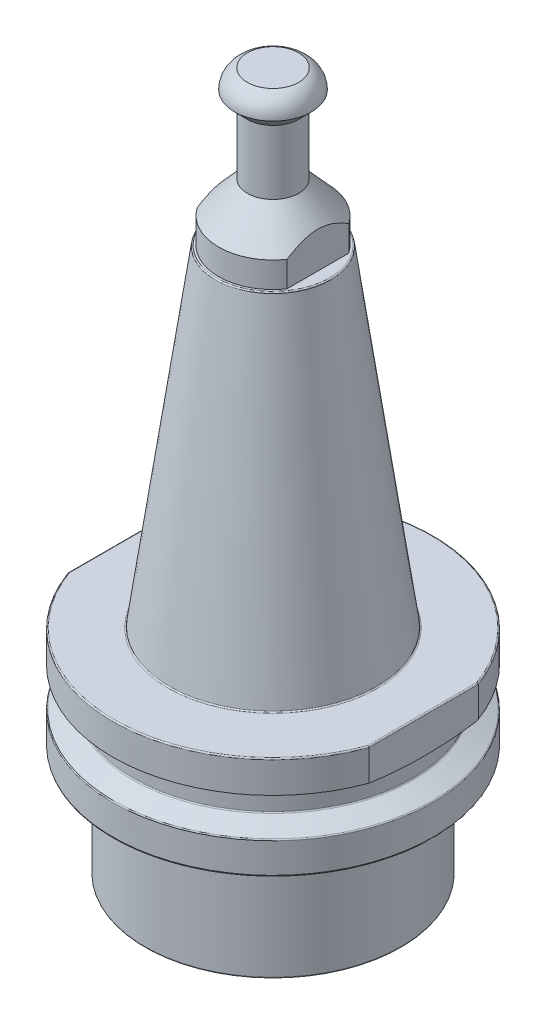
SolidWorks part; units mm, degrees
ref_plane "Спереди" through (0, 0, 0) normal (0, 0, 1) x (1, 0, 0)
ref_plane "Сверху" through (0, 0, 0) normal (0, 1, 0) x (1, 0, 0)
ref_plane "Справа" through (0, 0, 0) normal (1, 0, 0) x (0, 0, -1)
sketch "Эскиз1" plane through (0, 0, 0) normal (0, 0, 1) x (1, 0, 0)
  line L0 (0, 0) -> (0, 122.8444) construction
  line L1 (0, 32.5) -> (11, 32.5)
  line L2 (11, 32.5) -> (16.25, 0)
  line L3 (16.25, 0) -> (20, 0)
  line L4 (20, 0) -> (20, 17.3)
  line L5 (20, 17.3) -> (25, 17.3)
  line L6 (25, 17.3) -> (25, 22.3)
  line L7 (25, 22.3) -> (21.75, 23.7)
  line L8 (21.75, 23.7) -> (21.75, 26.9)
  line L9 (21.75, 26.9) -> (25, 28.3)
  line L10 (25, 28.3) -> (25, 33.3)
  line L11 (25, 33.3) -> (16.2, 33.3)
  line L12 (16.2, 33.3) -> (9, 85)
  line L13 (9, 85) -> (8.5, 85)
  line L14 (8.5, 85) -> (8.5, 89)
  line L15 (8.5, 89) -> (4, 94)
  line L16 (4, 94) -> (4, 104)
  line L17 (4, 104) -> (6, 106)
  line L18 (0, 109) -> (4, 109)
  line L19 (0, 32.5) -> (0, 109)
  arc A0 (6, 106) -> (4, 109) centre (2.7784, 106.0189) ccw
  dimension "D1" = 32.5
  dimension "D2" = 16.25
  dimension "D3" = 11
  dimension "D4" = 20
  dimension "D5" = 17.3
  dimension "D6" = 25
  dimension "D7" = 25
  dimension "D8" = 21.75
  dimension "D9" = 5
  dimension "D10" = 6.4
  dimension "D11" = 5
  dimension "D12" = 16
  dimension "D13" = 6.4
  dimension "D14" = 16.2
  dimension "D15" = 85
  dimension "D16" = 9
  dimension "D17" = 8.5
  dimension "D18" = 4
  dimension "D19" = 5
  dimension "D20" = 4
  dimension "D21" = 10
  dimension "D22" = 6
  dimension "D23" = 2
  dimension "D24" = 4
  dimension "D25" = 109
revolve "Повернуть1" add sketch "Эскиз1" angle 360 about L0
sketch "Эскиз2" plane through (0, 33.3, 0) normal (0, 1, 0) x (1, 0, 0)
  line L1 (-23.5, 28.4103) -> (-46.2398, 28.4103)
  line L2 (-23.5, 28.4103) -> (-23.5, -18.7456)
  line L3 (-23.5, -18.7456) -> (-46.2398, -18.7456)
  line L4 (-46.2398, 28.4103) -> (-46.2398, -18.7456)
  line L5 (23.5, 27.8272) -> (41.9396, 27.8272)
  line L6 (23.5, 27.8272) -> (23.5, -22.3169)
  line L7 (23.5, -22.3169) -> (41.9396, -22.3169)
  line L8 (41.9396, 27.8272) -> (41.9396, -22.3169)
  circle A0 centre (0, 0) radius 25 construction
  dimension "D1" = 23.5
  dimension "D2" = 23.5
extrude "Вырез-Вытянуть1" cut sketch "Эскиз2" against normal blind 10
sketch "Эскиз3" plane through (0, 85, 0) normal (0, 1, 0) x (1, 0, 0)
  line L1 (-7, 6.2089) -> (-12.3853, 6.2089)
  line L2 (-7, 6.2089) -> (-7, -7.7547)
  line L3 (-7, -7.7547) -> (-12.3853, -7.7547)
  line L4 (-12.3853, 6.2089) -> (-12.3853, -7.7547)
  line L5 (7, 7.5671) -> (14.0056, 7.5671)
  line L6 (7, 7.5671) -> (7, -8.8747)
  line L7 (7, -8.8747) -> (14.0056, -8.8747)
  line L8 (14.0056, 7.5671) -> (14.0056, -8.8747)
  circle A0 centre (0, 0) radius 9 construction
  dimension "D1" = 7
  dimension "D2" = 7
extrude "Вырез-Вытянуть2" cut sketch "Эскиз3" along normal blind 11
fillet "Скругление1" radius 0.2 13 edges at (0, 23.7, -21.75) (0, 26.9, -21.75) (0, 33.3, -16.2) (0, 33.3, -25) (0, 33.3, 25) (-23.5, 33.3, 0) (23.5, 33.3, 0) (0, 0, -16.25) (0, 0, -20) (0, 22.3, -25) (0, 28.3, -25) (0, 17.3, -25) (0, 85, -9)
